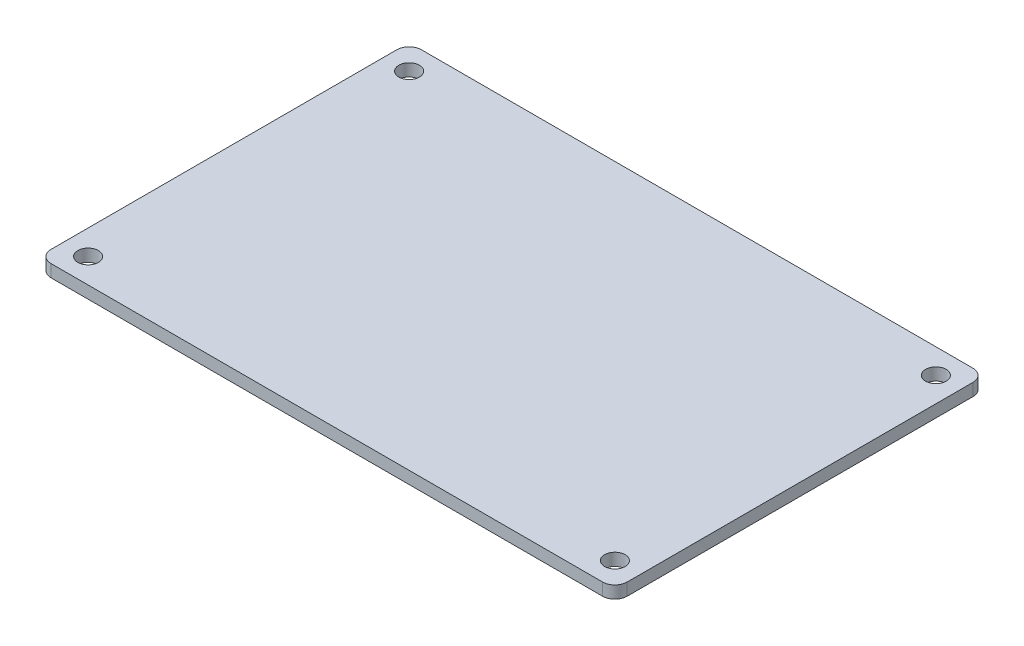
SolidWorks part; units mm, degrees
ref_plane "Спереди" through (0, 0, 0) normal (0, 0, 1) x (1, 0, 0)
ref_plane "Сверху" through (0, 0, 0) normal (0, 1, 0) x (1, 0, 0)
ref_plane "Справа" through (0, 0, 0) normal (1, 0, 0) x (0, 0, -1)
sketch "Эскиз1" plane through (0, 0, 0) normal (0, 1, 0) x (1, 0, 0)
  circle A0 centre (-34.925, 23.7282) radius 3
  circle A1 centre (-34.925, 23.7282) radius 6
  circle A2 centre (40.005, 23.7282) radius 3
  circle A3 centre (40.005, 23.7282) radius 6
  circle A4 centre (41.275, -24.5318) radius 3
  circle A5 centre (41.275, -24.5318) radius 6
  circle A6 centre (-41.275, -24.5318) radius 3
  circle A7 centre (-41.275, -24.5318) radius 6
extrude "Бобышка-Вытянуть1" add sketch "Эскиз1" against normal blind 9
sketch "Эскиз2" plane through (0, 0, 0) normal (0, 1, 0) x (1, 0, 0)
  line L0 (69.7259, 44.2184) -> (-70.2741, 44.2184)
  line L5 (69.7259, 44.2184) -> (69.7259, -45.7816)
  line L6 (69.7259, -45.7816) -> (-70.2741, -45.7816)
  line L7 (-70.2741, 44.2184) -> (-70.2741, -45.7816)
  line L8 (-0.2741, 44.2184) -> (-0.2741, -45.7816) construction
  line L10 (69.7259, -0.7816) -> (-70.2741, -0.7816) construction
  circle A0 centre (-64.2741, 38.2184) radius 2.5
  circle A1 centre (63.7259, 38.2184) radius 2.5
  circle A2 centre (63.7259, -39.7816) radius 2.5
  circle A3 centre (-64.2741, -39.7816) radius 2.5
  dimension "D1" = 6
  dimension "D5" = 5
  dimension "D2" = 6
  dimension "D3" = 140
  dimension "D4" = 90
extrude "Бобышка-Вытянуть2" add sketch "Эскиз2" against normal blind 3
fillet "Скругление1" radius 3 4 edges at (69.7259, -1.5, -44.2184) (69.7259, -1.5, 45.7816) (-70.2741, -1.5, -44.2184) (-70.2741, -1.5, 45.7816)
